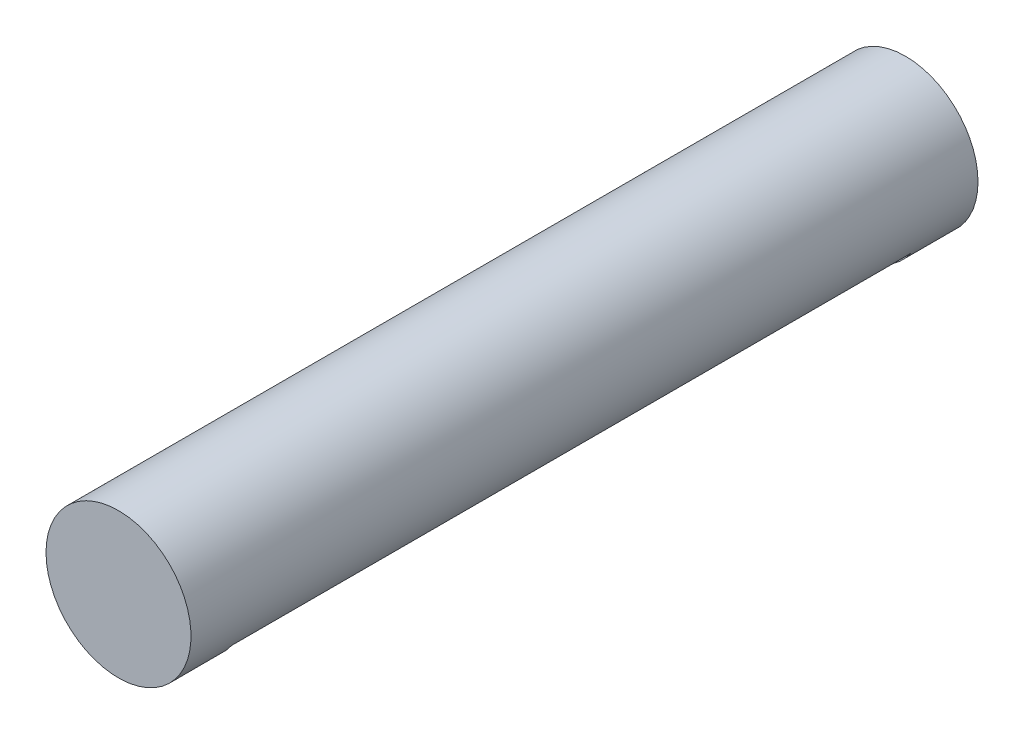
SolidWorks part; units mm, degrees
ref_plane "Plano frontal" through (0, 0, 0) normal (0, 0, 1) x (1, 0, 0)
ref_plane "Plano superior" through (0, 0, 0) normal (0, 1, 0) x (1, 0, 0)
ref_plane "Plano direito" through (0, 0, 0) normal (1, 0, 0) x (0, 0, -1)
sketch "Esboço1" plane through (0, 0, 0) normal (0, 0, 1) x (1, 0, 0)
  circle A0 centre (200, -240) radius 35 construction
  circle A1 centre (200, -240) radius 35
extrude "Ressalto-extrusão1" add sketch "Esboço1" along normal up to surface (380 mm away)
sketch "Esboço2" plane through (0, -270, 0) normal (0, -1, 0) x (1, 0, 0)
  line L0 (257.6628, 25) -> (142.3372, 25) construction
  line L1 (141.6409, 26) -> (259.6074, 26)
  line L2 (141.6409, 26) -> (141.6409, 354)
  line L3 (141.6409, 354) -> (259.6074, 354)
  line L4 (259.6074, 26) -> (259.6074, 354)
  line L5 (142.3372, 355) -> (257.6628, 355) construction
  dimension "D1" = 1
  dimension "D2" = 1
extrude "Corte-extrusão1" cut sketch "Esboço2" against normal blind 10 and the other way through all
